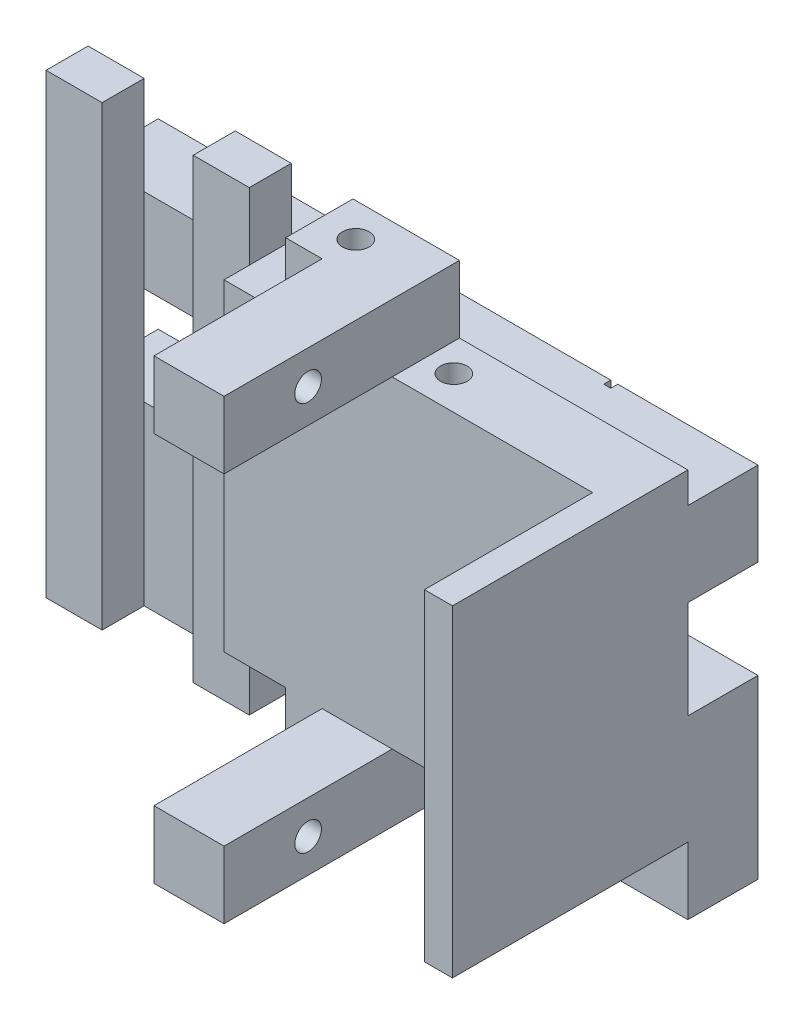
SolidWorks part; units mm, degrees
ref_plane "前视基准面" through (0, 0, 0) normal (0, 0, 1) x (1, 0, 0)
ref_plane "上视基准面" through (0, 0, 0) normal (0, 1, 0) x (1, 0, 0)
ref_plane "右视基准面" through (0, 0, 0) normal (1, 0, 0) x (0, 0, -1)
other "Configuration Table"
sketch "草图1" plane through (0, 0, 0) normal (0, 0, 1) x (1, 0, 0)
  line L0 (12, 0) -> (28.3, 0)
  line L1 (0, 0) -> (4.4, 0)
  line L2 (0, 0) -> (0, -23)
  line L3 (0, -23) -> (4.4, -23)
  line L4 (28.3, 0) -> (28.3, -23)
  line L6 (12, 0) -> (12, 4.8)
  line L7 (12, 4.8) -> (4.4, 4.8)
  line L8 (4.4, 0) -> (4.4, 4.8)
  line L10 (12, -23) -> (12, -27.8)
  line L11 (12, -27.8) -> (4.4, -27.8)
  line L12 (4.4, -23) -> (4.4, -27.8)
  line L13 (12, -23) -> (28.3, -23)
  dimension "D1" = 28.3
  dimension "D2" = 23
  dimension "D3" = 16.3
  dimension "D4" = 16.3
  dimension "D5" = 7.6
  dimension "D6" = 7.6
  dimension "D7" = 4.8
  dimension "D8" = 4.8
extrude "凸台-拉伸1" add sketch "草图1" along normal blind 4.8
sketch "草图2" plane through (0, 0, 4.8) normal (0, 0, 1) x (1, 0, 0)
  line L0 (12, -23) -> (28.3, -23) construction
  line L1 (12, 4.8) -> (7, 4.8)
  line L2 (12, 4.8) -> (12, 0)
  line L3 (12, 0) -> (7, 0)
  line L4 (7, 4.8) -> (7, 0)
  line L5 (12, -27.8) -> (7, -27.8)
  line L6 (12, -27.8) -> (12, -23)
  line L7 (12, -23) -> (7, -23)
  line L8 (7, -27.8) -> (7, -23)
  line L9 (28.3, 0) -> (26.3, 0)
  line L10 (28.3, 0) -> (28.3, -23)
  line L11 (28.3, -23) -> (26.3, -23)
  line L12 (26.3, 0) -> (26.3, -23)
  dimension "D1" = 2
  dimension "D2" = 5
  dimension "D3" = 5
extrude "凸台-拉伸2" add sketch "草图2" along normal blind 12
sketch "草图3" plane through (7, 0, 0) normal (-1, 0, 0) x (0, 0, 1)
  line L0 (10.8, 4.8) -> (10.8, -49995.2) construction
  line L1 (16.8, 4.8) -> (4.8, 4.8) construction
  line L2 (16.8, -27.8) -> (4.8, -27.8) construction
  line L3 (16.8, -25.4) -> (-49983.2, -25.4) construction
  line L4 (16.8, -23) -> (16.8, -27.8) construction
  line L5 (16.8, 2.4) -> (-49983.2, 2.4) construction
  line L6 (16.8, 4.8) -> (16.8, 0) construction
  circle A0 centre (10.8, 2.4) radius 0.95
  circle A1 centre (10.8, -25.4) radius 0.95
  point P4 (10.8, 4.8)
  point P7 (10.8, -27.8)
  point P12 (16.8, -25.4)
  point P17 (16.8, 2.4)
  dimension "D1" = 1.9
  dimension "D2" = 1.9
extrude "切除-拉伸1" cut sketch "草图3" against normal blind 5
sketch "草图6" plane through (0, 0, 0) normal (0, 1, 0) x (1, 0, 0)
  line L0 (12, -4.8) -> (12, 0) construction
  line L1 (28.3, 0) -> (12, 0) construction
  circle A0 centre (14, -2.4) radius 0.95
  dimension "D3" = 1.9
  dimension "D1" = 2
  dimension "D2" = 2.4
extrude "切除-拉伸4" cut sketch "草图6" against normal blind 32
sketch "草图7" plane through (0, 0, 0) normal (0, 0, -1) x (-1, 0, 0)
  line L1 (-28.3, -23) -> (-28.3, 0) construction
  line L2 (0, 0) -> (0, -23) construction
  line L3 (-28.3, -2.2) -> (14.5, -2.2)
  line L4 (-28.3, -2.2) -> (-28.3, -8.2)
  line L5 (-28.3, -8.2) -> (14.5, -8.2)
  line L6 (14.5, -2.2) -> (14.5, -8.2)
  line L12 (-28.3, 0) -> (-12, 0) construction
  dimension "D1" = 6
  dimension "D2" = 2.2
  dimension "D3" = 14.5
extrude "凸台-拉伸3" add sketch "草图7" along normal blind 5
sketch "草图8" plane through (0, 0, 0) normal (0, 0, 1) x (1, 0, 0)
  line L0 (-14.5, -8.2) -> (-14.5, -2.2) construction
  line L1 (0, 4.8) -> (-4, 4.8)
  line L2 (0, 4.8) -> (0, -27.8)
  line L3 (0, -27.8) -> (-4, -27.8)
  line L4 (-4, 4.8) -> (-4, -27.8)
  line L5 (-14.5, 4.8) -> (-10.5, 4.8)
  line L6 (-14.5, 4.8) -> (-14.5, -27.8)
  line L7 (-14.5, -27.8) -> (-10.5, -27.8)
  line L8 (-10.5, 4.8) -> (-10.5, -27.8)
  line L9 (9.5, 4.8) -> (-49990.5, 4.8) construction
  line L10 (12, 4.8) -> (7, 4.8) construction
  line L11 (7, 4.8) -> (4.4, 4.8) construction
  line L12 (9.5, -27.8) -> (-49990.5, -27.8) construction
  line L13 (7, -27.8) -> (12, -27.8) construction
  line L14 (4.4, -27.8) -> (7, -27.8) construction
  line L15 (0, 0) -> (0, -23) construction
  point P14 (9.5, 4.8)
  point P17 (5.7, 4.8)
  point P22 (9.5, -27.8)
  point P25 (5.7, -27.8)
  dimension "D1" = 4
  dimension "D2" = 4
extrude "凸台-拉伸4" add sketch "草图8" along normal blind 3
sketch "草图9" plane through (0, 0, 0) normal (0, 0, -1) x (-1, 0, 0)
  line L0 (-28.3, 0) -> (-12, 0) construction
  line L1 (-36.95, -15.2) -> (49963.05, -15.2) construction
  line L2 (14.5, -8.2) -> (14.5, -27.8) construction
  line L3 (14.5, -15.2) -> (-28.3, -15.2)
  line L4 (14.5, -15.2) -> (14.5, -27.8)
  line L5 (14.5, -27.8) -> (-28.3, -27.8)
  line L6 (-28.3, -15.2) -> (-28.3, -27.8)
  line L7 (-4.4, -27.8) -> (-12, -27.8) construction
  line L8 (-28.3, -23) -> (-28.3, -8.2) construction
  dimension "D1" = 15.2
extrude "凸台-拉伸6" add sketch "草图9" along normal blind 5
sketch "草图11" plane through (0, 4.8, 0) normal (0, 1, 0) x (1, 0, 0)
  line L0 (14, -2.4) -> (14, -50002.4) construction
  line L1 (7, -1.8818) -> (7, -50001.8818) construction
  line L2 (14, -2.4) -> (50014, -2.4) construction
  circle A0 centre (7, -2.4) radius 0.95
  dimension "D2" = 1.9
  dimension "D1" = 7
extrude "切除-拉伸5" cut sketch "草图11" against normal through all
sketch "草图12" plane through (0, 0, -5) normal (0, 0, -1) x (-1, 0, 0)
  line L0 (4, -2.2) -> (-28.3, -2.2) construction
  line L1 (-18.3, -2.2) -> (-17.8, -2.2)
  line L2 (-18.3, -2.2) -> (-18.3, -27.8)
  line L3 (-18.3, -27.8) -> (-17.8, -27.8)
  line L4 (-17.8, -2.2) -> (-17.8, -27.8)
  line L5 (-28.3, -27.8) -> (14.5, -27.8) construction
  line L6 (-28.3, -2.2) -> (-28.3, -8.2) construction
  line L7 (-1, -2.2) -> (-0.5, -2.2)
  line L8 (-1, -2.2) -> (-1, -27.8)
  line L9 (-1, -27.8) -> (-0.5, -27.8)
  line L10 (-0.5, -2.2) -> (-0.5, -27.8)
  line L11 (14.5, -8.2) -> (14.5, -2.2) construction
  dimension "D1" = 0.5
  dimension "D2" = 0.5
  dimension "D3" = 10
  dimension "D4" = 15
extrude "切除-拉伸6" cut sketch "草图12" against normal blind 0.5
